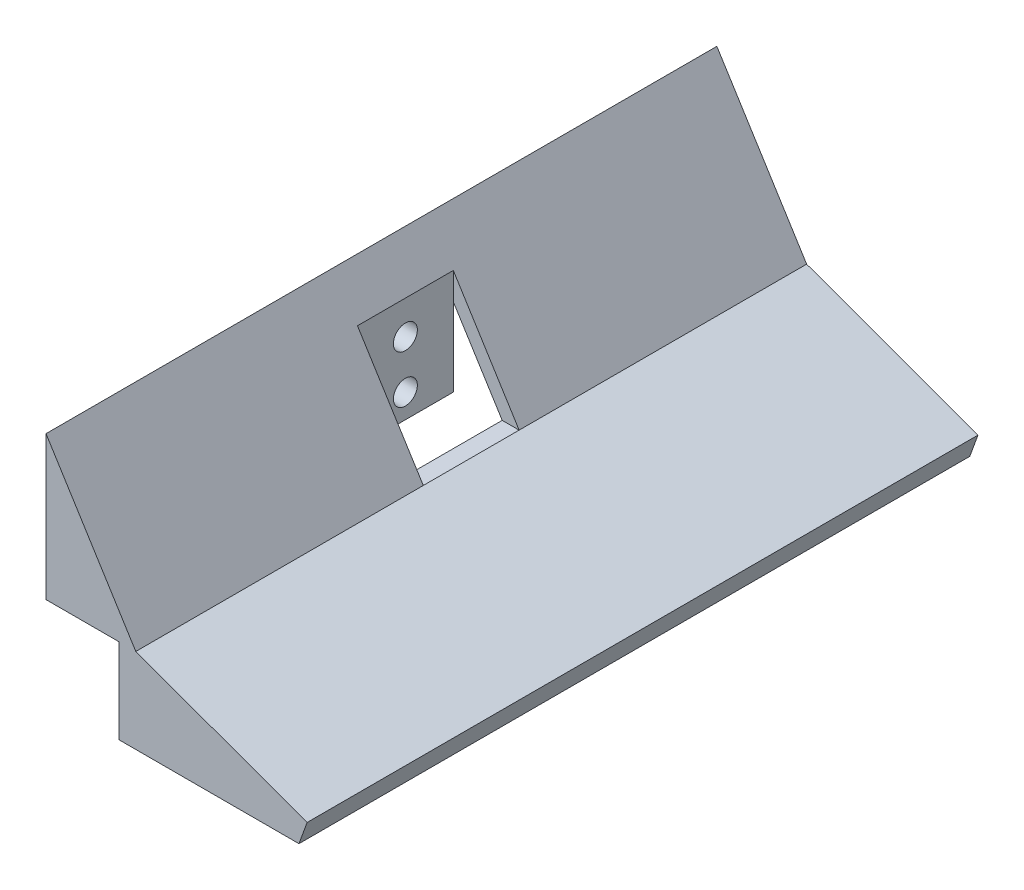
SolidWorks part; units mm, degrees
ref_plane "정면" through (0, 0, 0) normal (0, 0, 1) x (1, 0, 0)
ref_plane "윗면" through (0, 0, 0) normal (0, 1, 0) x (1, 0, 0)
ref_plane "우측면" through (0, 0, 0) normal (1, 0, 0) x (0, 0, -1)
sketch "스케치1" plane through (0, 0, 0) normal (0, 0, 1) x (1, 0, 0)
  line L0 (-19.5974, 21.928) -> (-19.5974, -8.072)
  line L1 (-19.5974, -8.072) -> (-4.3974, -8.072)
  line L2 (-4.3974, -8.072) -> (-19.5974, 21.928)
  dimension "D1" = 30
extrude "보스-돌출1" add sketch "스케치1" along normal blind 5
sketch "스케치2" plane through (0, 0, 5) normal (0, 0, 1) x (1, 0, 0)
  line L0 (-19.5974, 21.928) -> (-0.8603, -8.072)
  line L1 (-0.8603, -8.072) -> (-4.3974, -8.072)
  line L2 (-4.3974, -8.072) -> (-24.5974, -8.072) construction
  line L3 (-19.5974, 21.928) -> (-19.5974, 16.2648)
  line L4 (-19.5974, 21.928) -> (-19.5974, -8.072) construction
  line L5 (-19.5974, 16.2648) -> (-4.3974, -8.072)
  dimension "D1" = 3
extrude "보스-돌출2" add sketch "스케치2" along normal blind 135 and the other way blind 5
sketch "스케치3" plane through (-4.2457, -2.6517, 0) normal (0.8482, 0.5297, 0) x (0, 0, -1)
  line L0 (-80, 28.9799) -> (-60, 28.9799)
  line L1 (-80, 28.9799) -> (-80, -6.3907)
  line L2 (-60, 28.9799) -> (-60, -6.3907)
  line L3 (-80, -6.3907) -> (-60, -6.3907)
  line L4 (-140, 28.9799) -> (0, 28.9799) construction
  line L5 (-140, -6.3907) -> (-140, 28.9799) construction
  line L6 (0, -6.3907) -> (0, 28.9799) construction
  line L7 (0, -6.3907) -> (-140, -6.3907) construction
  dimension "D1" = 60
  dimension "D2" = 60
extrude "컷-돌출1" cut sketch "스케치3" against normal blind 135
sketch "스케치4" plane through (-19.5974, 0, 0) normal (-1, 0, 0) x (0, 0, 1)
  line L0 (60, 21.928) -> (80, 21.928)
  line L1 (60, 21.928) -> (60, -8.072)
  line L2 (80, 21.928) -> (80, -8.072)
  line L3 (60, -8.072) -> (80, -8.072)
  line L4 (80, -8.072) -> (140, -8.072) construction
extrude "보스-돌출3" add sketch "스케치4" against normal blind 5
sketch "스케치5" plane through (0, 0, 80) normal (0, 0, 1) x (1, 0, 0)
  line L0 (-19.5974, 21.928) -> (-14.5974, 21.928)
  line L1 (-14.5974, 21.928) -> (-14.5974, 13.9224)
  line L2 (-14.5974, 13.9224) -> (-19.5974, 21.928)
extrude "컷-돌출2" cut sketch "스케치5" against normal blind 78
sketch "스케치6" plane through (-19.5974, 0, 0) normal (-1, 0, 0) x (0, 0, 1)
  circle A0 centre (70, -3.072) radius 2.5
  circle A1 centre (70, 6.928) radius 2.5
extrude "컷-돌출3" cut sketch "스케치6" against normal blind 78
sketch "스케치7" plane through (0, 0, 140) normal (0, 0, 1) x (1, 0, 0)
  line L0 (-0.8603, -8.072) -> (-19.5974, 21.928)
  line L1 (-19.5974, 21.928) -> (-19.5974, -8.072)
  line L2 (-19.5974, -8.072) -> (-0.8603, -8.072)
extrude "보스-돌출4" add sketch "스케치7" against normal blind 5
sketch "스케치8" plane through (0, 0, 140) normal (0, 0, 1) x (1, 0, 0)
  line L0 (-0.8603, -8.072) -> (34.9004, -21.0879)
  line L1 (34.9004, -21.0879) -> (33.1903, -25.7864)
  line L2 (-4.3974, -148.072) -> (-4.3974, -8.072) construction
  line L6 (33.1903, -25.7864) -> (-4.3974, -12.1056)
  line L7 (-0.8603, -8.072) -> (-4.3974, -8.072)
  line L8 (-19.5974, -8.072) -> (-0.8603, -8.072) construction
  line L9 (-4.3974, -8.072) -> (-4.3974, -12.1056)
  line L10 (-4.3974, -12.1056) -> (-4.3331, -12.1149)
  dimension "D1" = 5
  dimension "D2" = 70
  dimension "D3" = 40
extrude "보스-돌출5" add sketch "스케치8" against normal blind 140
sketch "스케치9" plane through (0, 0, 140) normal (0, 0, 1) x (1, 0, 0)
  line L0 (33.1903, -25.7864) -> (-4.3974, -25.7864)
  line L1 (-4.3974, -148.072) -> (-4.3974, -8.072) construction
  line L2 (-4.3974, -25.7864) -> (-4.3974, -8.072)
  line L3 (-4.3974, -8.072) -> (33.1903, -25.7864)
extrude "보스-돌출6" add sketch "스케치9" against normal blind 5
sketch "스케치10" plane through (0, 0, 0) normal (0, 0, -1) x (-1, 0, 0)
  line L0 (-33.1903, -25.7864) -> (4.3974, -25.7864)
  line L1 (4.3974, -8.072) -> (4.3974, -148.072) construction
  line L2 (4.3974, -25.7864) -> (4.3974, -10.0888)
  line L3 (4.3974, -8.072) -> (4.3974, -12.1056) construction
  line L4 (4.3974, -10.0888) -> (-33.1903, -25.7864)
extrude "보스-돌출7" add sketch "스케치10" against normal blind 5
